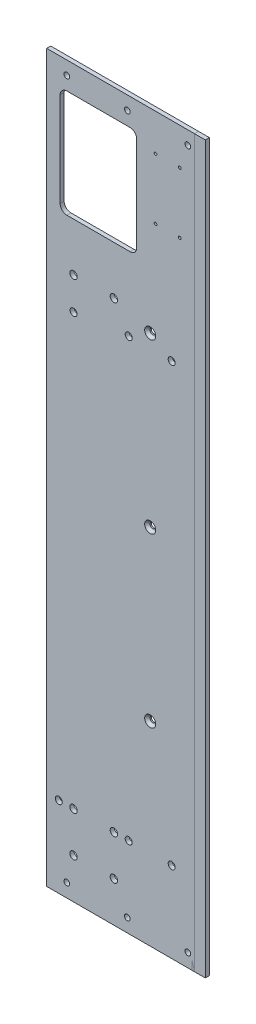
SolidWorks part; units mm, degrees
material "Thornel Mat VMA"
ref_plane "Front" through (0, 0, 0) normal (0, 0, 1) x (1, 0, 0)
ref_plane "Top" through (0, 0, 0) normal (0, 1, 0) x (1, 0, 0)
ref_plane "Right" through (0, 0, 0) normal (1, 0, 0) x (0, 0, -1)
sketch "草图1" plane through (0, 0, 0) normal (0, 0, 1) x (1, 0, 0)
  line L1 (-75, -270) -> (75, -270)
  line L2 (-75, -270) -> (-75, 270)
  line L3 (-75, 270) -> (75, 270)
  line L4 (75, -270) -> (75, 270)
  line L5 (-75, -270) -> (75, 270) construction
  line L6 (-75, 270) -> (75, -270) construction
  point P0 (0, 0)
  dimension "D1" = 150
  dimension "D2" = 540
extrude "凸台-拉伸1" add sketch "草图1" along normal blind 3
sketch "草图2" plane through (0, 0, 0) normal (0, 0, -1) x (-1, 0, 0)
  line L0 (-75, 0) -> (75, 0) construction
  line L1 (-75, -270) -> (-75, 270) construction
  line L2 (75, 270) -> (75, -270) construction
  line L3 (75, -270) -> (-75, -270) construction
  line L4 (0, -270) -> (0, -312.3628) construction
  line L5 (0, 270) -> (0, 297.7999) construction
  line L6 (-75, 270) -> (75, 270) construction
  circle A2 centre (65, -260) radius 2.1
  circle A3 centre (-70, -260) radius 2.1
  circle A6 centre (65, 260) radius 2.1
  circle A7 centre (-70, 260) radius 2.1
  circle A8 centre (-25, -260) radius 2.1
  circle A9 centre (20, -260) radius 2.1
  circle A10 centre (20, 260) radius 2.1
  circle A11 centre (-25, 260) radius 2.1
  circle A16 centre (15, 196.5) radius 1.6
  circle A17 centre (15, 188.5) radius 1.6
  circle A18 centre (-15, 196.5) radius 1.6
  circle A19 centre (-15, 188.5) radius 1.6
  dimension "D2" = 45
  dimension "D3" = 3.2
  dimension "D4" = 4.2
  dimension "D5" = 10
  dimension "D6" = 10
  dimension "D7" = 4.2
  dimension "D8" = 5
  dimension "D9" = 10
  dimension "D10" = 30
  dimension "D11" = 8
  dimension "D12" = 73.5
  dimension "D13" = 45
extrude "切除-拉伸1" cut sketch "草图2" against normal through all
sketch "草图3" [suppressed] plane through (0, 0, 3) normal (0, 0, 1) x (1, 0, 0)
  line L1 (75, -270) -> (75, 270) construction
  circle A0 centre (65, 30) radius 1.5
  circle A1 centre (65, -30) radius 1.5
  dimension "D1" = 3
  dimension "D2" = 10
  dimension "D3" = 30
  dimension "D4" = 3
  dimension "D5" = 30
  dimension "D6" = 10
sketch "草图4" plane through (0, 0, 3) normal (0, 0, 1) x (1, 0, 0)
  line L0 (42, 0) -> (140.7159, 0) construction
  line L1 (75, -270) -> (75, 270) construction
  line L2 (0, 270) -> (0, -270) construction
  line L3 (75, 270) -> (-75, 270) construction
  line L4 (-75, -270) -> (75, -270) construction
  line L5 (-42, 0) -> (-140.7159, 0) construction
  circle A0 centre (42, 125) radius 2.1
  circle A1 centre (42, -125) radius 2.1
  circle A2 centre (42, 0) radius 2.1
  circle A3 centre (-42, 0) radius 2.1
  circle A4 centre (-42, -125) radius 2.1
  circle A5 centre (-42, 125) radius 2.1
  dimension "D1" = 250
  dimension "D2" = 4.2
  dimension "D3" = 4.2
  dimension "D4" = 33
  dimension "D5" = 33
extrude "切除-拉伸2" cut sketch "草图4" against normal up to next
chamfer "倒角1" distance 2 angle 45 3 edges at (44.1, 0, 3) (39.9, -125, 3) (44.1, 125, 3)
sketch "草图6" plane through (0, 0, 3) normal (0, 0, 1) x (1, 0, 0)
  line L0 (0, -286.6484) -> (0, 69.1326) construction
  line L1 (-75, -270) -> (75, -270) construction
  line L2 (-75, 270) -> (-75, -270) construction
  line L3 (75, -270) -> (75, 270) construction
  line L6 (75, 270) -> (-75, 270) construction
  circle A1 centre (26, -210) radius 2.6
  circle A4 centre (-26, -210) radius 2.6
  circle A5 centre (58, -210) radius 2.6
  circle A6 centre (-58, -210) radius 2.6
  circle A9 centre (-47, 110) radius 2.6
  circle A10 centre (-15, 110) radius 2.6
  circle A11 centre (26, 115) radius 2.6
  circle A12 centre (58, 115) radius 2.6
  dimension "D1" = 5.2
  dimension "D2" = 17
  dimension "D3" = 60
  dimension "D4" = 32
  dimension "D5" = 5.2
  dimension "D6" = 5.2
  dimension "D7" = 5.2
  dimension "D8" = 5.2
  dimension "D9" = 32
  dimension "D10" = 17
  dimension "D11" = 32
  dimension "D12" = 28
  dimension "D14" = 160
  dimension "D15" = 155
  dimension "D16" = 155
extrude "切除-拉伸4" cut sketch "草图6" against normal up to next
sketch "草图7" plane through (0, 0, 3) normal (0, 0, 1) x (1, 0, 0)
  line L4 (75, -270) -> (75, 270)
  line L5 (75, 270) -> (-75, 270)
  line L6 (-75, 270) -> (-75, -270)
  line L7 (-75, -270) -> (75, -270)
  line L8 (75, -270) -> (75, 270)
  line L9 (75, 270) -> (-75, 270)
  line L10 (-75, 270) -> (-75, -270)
  line L11 (-75, -270) -> (75, -270)
  circle A2 centre (-15, 134) radius 2.75
  circle A3 centre (15, 134) radius 2.75
  dimension "D2" = 136
  dimension "D3" = 5.5
  dimension "D5" = 30
  dimension "D6" = 5.5
  dimension "D7" = 60
  dimension "D4" = 136
  dimension "D1" = 0
extrude "切除-拉伸5" cut sketch "草图7" against normal up to next contours A2 | A3
sketch "草图8" plane through (0, 0, 3) normal (0, 0, 1) x (1, 0, 0)
  line L4 (75, -270) -> (75, 270)
  line L5 (75, 270) -> (-75, 270)
  line L6 (-75, 270) -> (-75, -270)
  line L7 (-75, -270) -> (75, -270)
  line L8 (75, -270) -> (75, 270)
  line L9 (75, 270) -> (-75, 270)
  line L10 (-75, 270) -> (-75, -270)
  line L11 (-75, -270) -> (75, -270)
  circle A2 centre (-15, -210) radius 2.75
  circle A3 centre (15, -210) radius 2.75
  dimension "D2" = 5.5
  dimension "D3" = 5.5
  dimension "D4" = 30
  dimension "D5" = 60
  dimension "D6" = 60
  dimension "D7" = 60
  dimension "D1" = 0
extrude "切除-拉伸6" cut sketch "草图8" against normal up to next contours A2 | A3
sketch "草图9" plane through (0, 0, 3) normal (0, 0, 1) x (1, 0, 0)
  line L0 (0, -270) -> (0, -79.9483) construction
  line L1 (-75, -270) -> (75, -270) construction
  circle A0 centre (-15, -240) radius 2.75
  circle A1 centre (15, -240) radius 2.75
  dimension "D1" = 5.5
  dimension "D2" = 30
  dimension "D3" = 30
extrude "切除-拉伸7" cut sketch "草图9" against normal blind 10
sketch "草图10" plane through (0, 0, 3) normal (0, 0, 1) x (1, 0, 0)
  line L0 (0, 270) -> (0, 151.6479) construction
  line L1 (75, 270) -> (-75, 270) construction
  line L2 (-25, 170) -> (-25, 250)
  line L3 (-25, 170) -> (25, 170)
  line L4 (0, 170) -> (0, 250)
  line L5 (-25, 250) -> (25, 250)
  line L6 (25, 170) -> (25, 250)
  line L8 (25, 250) -> (32, 250)
  line L9 (25, 250) -> (25, 170)
  line L10 (25, 170) -> (32, 170)
  line L11 (32, 250) -> (32, 170)
  circle M23 centre (-15, 196.5) radius 1.6
  circle M28 centre (15, 188.5) radius 1.6
  circle M29 centre (15, 196.5) radius 1.6
  circle M30 centre (-15, 188.5) radius 1.6
  dimension "D1" = 50
  dimension "D2" = 20
  dimension "D3" = 80
  dimension "D4" = 7
extrude "切除-拉伸8" cut sketch "草图10" against normal blind 10 contours L5 L2 L3 L4 M30 M23 | L3 L6 L5 L4 M28 M29 | L11 L8 L6 L10
fillet "圆角1" radius 5 4 edges at (-25, 170, 1.5) (-25, 250, 1.5) (32, 170, 1.5) (32, 250, 1.5)
sketch "草图11" plane through (0, 0, 3) normal (0, 0, 1) x (1, 0, 0)
  line L0 (55, 266.5246) -> (55, 192.9358) construction
  line L1 (-66.7226, 220) -> (-27.8973, 220) construction
  line L2 (-75, 270) -> (-75, -270) construction
  line L3 (75, 270) -> (-75, 270) construction
  circle A0 centre (46, 242.6) radius 1
  circle A1 centre (64, 242.6) radius 1
  circle A2 centre (64, 197.4) radius 1
  circle A3 centre (46, 197.4) radius 1
  dimension "D1" = 2
  dimension "D2" = 18
  dimension "D3" = 45.2
  dimension "D4" = 130
  dimension "D5" = 50
extrude "切除-拉伸9" cut sketch "草图11" against normal blind 4
sketch "草图13" plane through (0, 0, 3) normal (0, 0, 1) x (1, 0, 0)
  line L0 (-35, 270) -> (-35, -270)
  line L1 (75, 270) -> (-75, 270) construction
  line L2 (-75, -270) -> (75, -270) construction
  line L4 (-35, 270) -> (-236.483, 270)
  line L5 (-35, 270) -> (-35, -387.7593)
  line L6 (-35, -387.7593) -> (-236.483, -387.7593)
  line L7 (-236.483, 270) -> (-236.483, -387.7593)
  circle A0 centre (-20, 260) radius 2.1 construction
  dimension "D1" = 15
extrude "切除-拉伸10" cut sketch "草图13" against normal blind 10
sketch "草图14" plane through (0, 0, 3) normal (0, 0, 1) x (1, 0, 0)
  line L0 (-35, -270) -> (75, -270) construction
  line L1 (73, 270) -> (83, 270)
  line L2 (73, 270) -> (73, -270)
  line L3 (73, -270) -> (83, -270)
  line L4 (83, 270) -> (83, -270)
  line L5 (75, -270) -> (75, 270) construction
  line L6 (75, 270) -> (-35, 270) construction
  dimension "D1" = 10
  dimension "D2" = 2
extrude "凸台-拉伸2" add sketch "草图14" against normal blind 3 separate body
